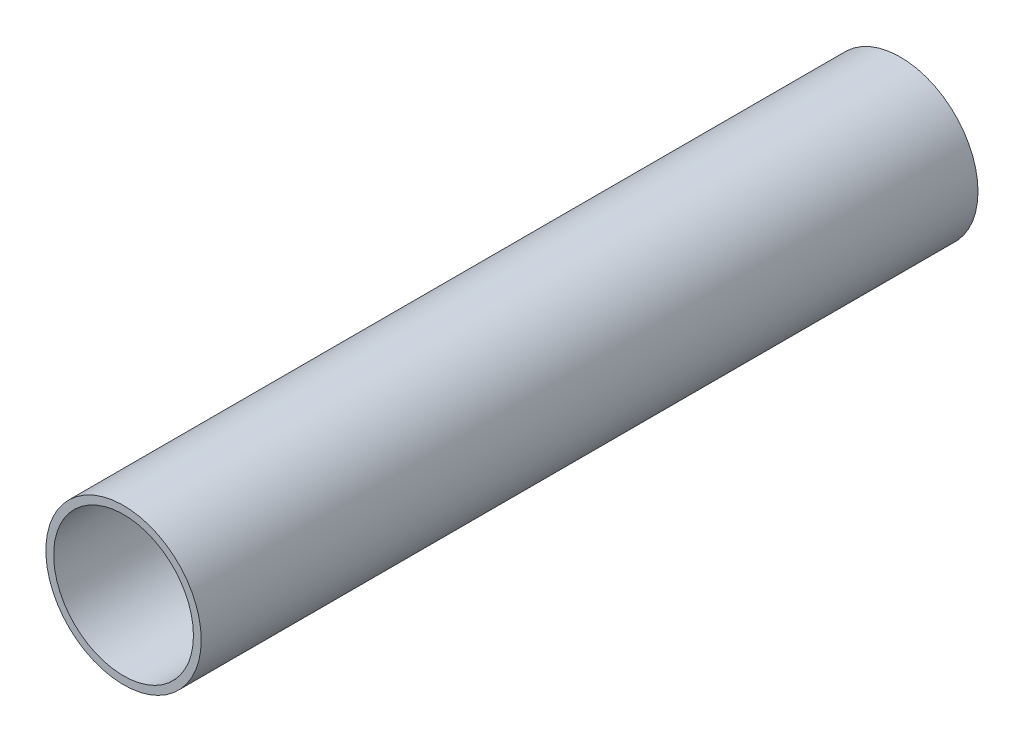
SolidWorks part; units mm, degrees
material "6063-T6"
ref_plane "Front Plane" through (0, 0, 0) normal (0, 0, 1) x (1, 0, 0)
ref_plane "Top Plane" through (0, 0, 0) normal (0, 1, 0) x (1, 0, 0)
ref_plane "Right Plane" through (0, 0, 0) normal (1, 0, 0) x (0, 0, -1)
sketch "Sketch1" plane through (0, 0, 0) normal (0, 0, 1) x (1, 0, 0)
  circle A0 centre (0, 0) radius 50
  circle A1 centre (0, 0) radius 45
  dimension "D1" = 90
  dimension "D2" = 100
extrude "Boss-Extrude1" add sketch "Sketch1" along normal blind 500
sketch "Sketch2" plane through (0, 0, 500) normal (0, 0, 1) x (1, 0, 0)
  circle A0 centre (0, 0) radius 45.15
  dimension "D1" = 90.3
extrude "Cut-Extrude1" [suppressed] cut sketch "Sketch2" against normal blind 20
sketch "Sketch3" plane through (0, 0, 0) normal (0, 0, -1) x (-1, 0, 0)
  circle A0 centre (0, 0) radius 45.15
  dimension "D1" = 90.3
extrude "Cut-Extrude2" [suppressed] cut sketch "Sketch3" against normal blind 20
